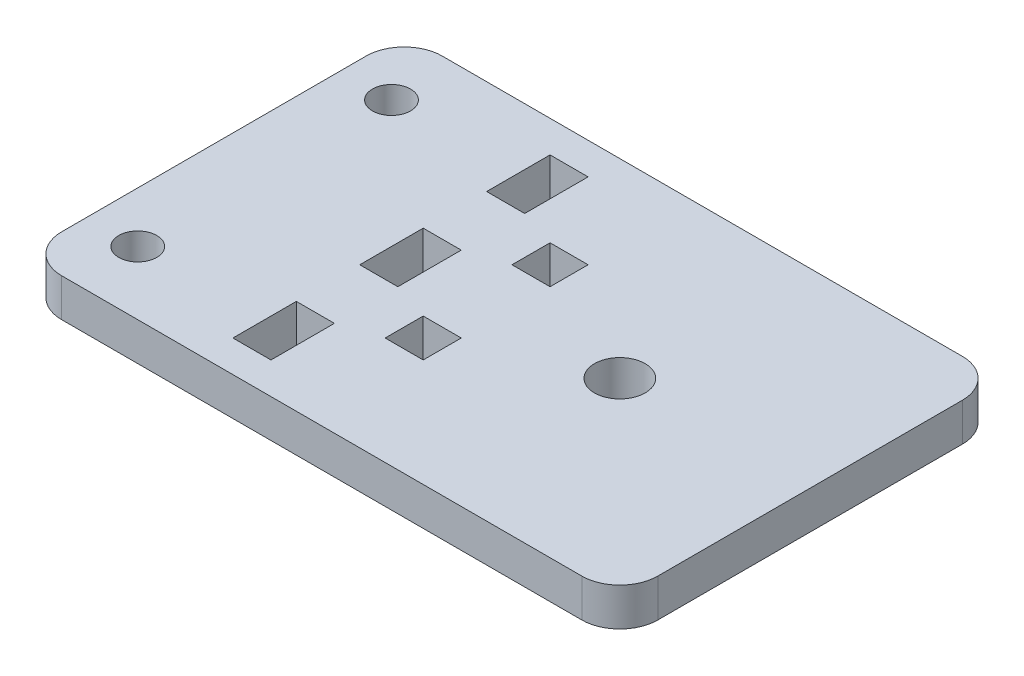
SolidWorks part; units mm, degrees
ref_plane "Front Plane" through (0, 0, 0) normal (0, 0, 1) x (1, 0, 0)
ref_plane "Top Plane" through (0, 0, 0) normal (0, 1, 0) x (1, 0, 0)
ref_plane "Right Plane" through (0, 0, 0) normal (1, 0, 0) x (0, 0, -1)
sketch "Sketch1" plane through (0, 0, 0) normal (0, 1, 0) x (1, 0, 0)
  line L1 (-8.5, 15) -> (8.5, 15)
  line L2 (-8.5, 15) -> (-8.5, -15)
  line L3 (-8.5, -15) -> (8.5, -15)
  line L4 (8.5, 15) -> (8.5, -15)
  line L5 (-8.5, 15) -> (8.5, -15) construction
  line L6 (-8.5, -15) -> (8.5, 15) construction
  point P0 (0, 0)
  dimension "D1" = 17
  dimension "D2" = 30
extrude "Boss-Extrude1" add sketch "Sketch1" along normal blind 3
sketch "Sketch2" plane through (0, 3, 0) normal (0, 1, 0) x (1, 0, 0)
  line L0 (8.5, 12.5) -> (5.5, 12.5)
  line L1 (8.5, -15) -> (8.5, 15) construction
  line L2 (5.5, 12.5) -> (5.5, 7.5)
  line L3 (5.5, 7.5) -> (8.5, 7.5)
  line L4 (8.5, 7.5) -> (8.5, 12.5)
  line L5 (8.5, 15) -> (-8.5, 15) construction
  line L6 (8.5, 2.5) -> (5.5, 2.5)
  line L7 (8.5, 2.5) -> (8.5, -2.5)
  line L8 (8.5, -2.5) -> (5.5, -2.5)
  line L9 (5.5, 2.5) -> (5.5, -2.5)
  line L10 (8.5, -7.5) -> (5.5, -7.5)
  line L11 (8.5, -7.5) -> (8.5, -12.5)
  line L12 (8.5, -12.5) -> (5.5, -12.5)
  line L13 (5.5, -7.5) -> (5.5, -12.5)
  line L14 (-8.5, -15) -> (8.5, -15) construction
  point P14 (5.5, 0)
  point P17 (5.5, 10)
  point P18 (5.5, -10)
  dimension "D1" = 5
  dimension "D2" = 5
  dimension "D3" = 5
  dimension "D4" = 15
  dimension "D5" = 5
  dimension "D6" = 5
  dimension "D7" = 3
  dimension "D8" = 3
  dimension "D9" = 3
extrude "Cut-Extrude1" cut sketch "Sketch2" against normal blind 3
sketch "Sketch3" plane through (0, 3, 0) normal (0, 1, 0) x (1, 0, 0)
  line L0 (-4.5, 17.5285) -> (-4.5, -19.8049) construction
  line L1 (-8.5, 15) -> (-8.5, -15) construction
  line L2 (8.5, 15) -> (-8.5, 15) construction
  line L3 (-8.5, -15) -> (8.5, -15) construction
  circle A0 centre (-4.5, 10) radius 1.5
  circle A1 centre (-4.5, -10) radius 1.5
  dimension "D4" = 3
  dimension "D5" = 3
  dimension "D1" = 4
  dimension "D2" = 5
  dimension "D3" = 5
extrude "Cut-Extrude2" cut sketch "Sketch3" against normal blind 3
fillet "Fillet1" radius 3 2 edges at (-8.5, 1.5, -15) (-8.5, 1.5, 15)
sketch "Sketch4" plane through (0, 3, 0) normal (0, 1, 0) x (1, 0, 0)
  line L0 (8.5, -15) -> (8.5, 15)
  line L1 (8.5, -15) -> (38.5, -15)
  line L2 (8.5, 15) -> (38.5, 15)
  line L3 (38.5, -15) -> (38.5, 15)
  line L4 (-8.5, 12) -> (-8.5, -12) construction
  dimension "D1" = 47
extrude "Boss-Extrude2" add sketch "Sketch4" against normal blind 3
fillet "Fillet2" radius 3 2 edges at (38.5, 1.5, -15) (38.5, 1.5, 15)
sketch "Sketch5" plane through (0, 3, 0) normal (0, 1, 0) x (1, 0, 0)
  line L0 (44.1019, 0) -> (13.5449, 0) construction
  line L1 (38.5, -12) -> (38.5, 12) construction
  circle A0 centre (23.5, 0) radius 2
  dimension "D1" = 4
  dimension "D2" = 15
extrude "Cut-Extrude3" cut sketch "Sketch5" against normal blind 3
sketch "Sketch6" plane through (0, 3, 0) normal (0, 1, 0) x (1, 0, 0)
  line L0 (11.5, 18.1393) -> (11.5, -18.5325) construction
  line L1 (8.5, 2.5) -> (8.5, -2.5) construction
  line L2 (11.5, 3.5) -> (11.5, 6.5)
  line L3 (11.5, 3.5) -> (14.5, 3.5)
  line L4 (11.5, 6.5) -> (14.5, 6.5)
  line L5 (14.5, 3.5) -> (14.5, 6.5)
  line L6 (11.5, -6.5) -> (11.5, -3.5)
  line L7 (11.5, -6.5) -> (14.5, -6.5)
  line L8 (11.5, -3.5) -> (14.5, -3.5)
  line L9 (14.5, -6.5) -> (14.5, -3.5)
  line L10 (35.5, 15) -> (-5.5, 15) construction
  line L11 (-5.5, -15) -> (35.5, -15) construction
  point P6 (14.5, 5)
  point P19 (14.5, -5)
  dimension "D1" = 3
  dimension "D2" = 3
  dimension "D3" = 3
  dimension "D4" = 3
  dimension "D5" = 3
  dimension "D6" = 10
  dimension "D7" = 10
extrude "Cut-Extrude4" cut sketch "Sketch6" against normal blind 10
